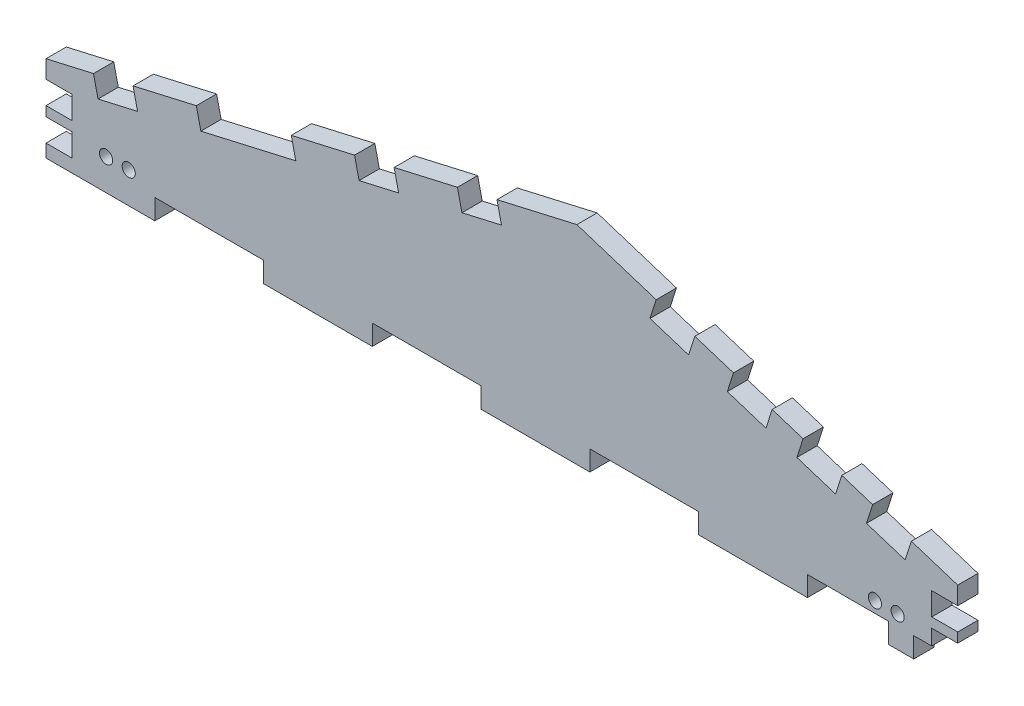
SolidWorks part; units mm, degrees
material "Maple"
ref_plane "Front Plane" through (0, 0, 0) normal (0, 0, 1) x (1, 0, 0)
ref_plane "Top Plane" through (0, 0, 0) normal (0, 1, 0) x (1, 0, 0)
ref_plane "Right Plane" through (0, 0, 0) normal (1, 0, 0) x (0, 0, -1)
sketch "Sketch2" plane through (0, 0, 0) normal (0, 0, 1) x (1, 0, 0)
  line L0 (11.7348, -6.731) -> (11.7348, 25.781)
  line L1 (-71.3232, -6.731) -> (71.3232, -6.731)
  line L2 (-71.3232, -6.731) -> (-71.3232, 6.731)
  line L3 (-71.3232, 6.731) -> (71.3232, 6.731)
  line L4 (71.3232, -6.731) -> (71.3232, 6.731)
  line L5 (-71.3232, -6.731) -> (71.3232, 6.731) construction
  line L6 (-71.3232, 6.731) -> (71.3232, -6.731) construction
  line L7 (-71.3232, 6.731) -> (11.7348, 25.781)
  line L8 (11.7348, 25.781) -> (71.3232, 6.731)
  line L9 (-71.3232, 6.731) -> (11.7348, 25.781)
  line L10 (71.3232, 6.731) -> (-71.3232, 6.731)
  line L11 (11.7348, 25.781) -> (71.3232, 6.731)
  line L12 (0, -17.8816) -> (0, 17.8816) construction
  line L13 (-71.3232, -4.699) -> (-67.2592, -4.699)
  line L14 (-71.3232, -4.699) -> (-71.3232, -1.143)
  line L15 (-71.3232, -1.143) -> (-67.2592, -1.143)
  line L16 (-67.2592, -4.699) -> (-67.2592, -1.143)
  line L17 (-71.3232, 0.381) -> (-67.2592, 0.381)
  line L18 (-71.3232, 0.381) -> (-71.3232, 3.937)
  line L19 (-71.3232, 3.937) -> (-67.2592, 3.937)
  line L20 (-67.2592, 0.381) -> (-67.2592, 3.937)
  line L22 (71.3232, 4.5729) -> (71.3232, 1.5826)
  line L29 (71.3232, -1.143) -> (67.2592, -1.143)
  line L30 (67.2592, -4.699) -> (67.2592, -1.143)
  line L31 (71.3232, -4.699) -> (67.2592, -4.699)
  line L32 (71.3232, -4.699) -> (71.3232, -1.143)
  line L33 (71.3232, 3.937) -> (67.2592, 3.937)
  line L34 (67.2592, 0.381) -> (67.2592, 3.937)
  line L35 (71.3232, 0.381) -> (67.2592, 0.381)
  line L36 (71.3232, 0.381) -> (71.3232, 3.937)
  point P0 (0, 0)
  dimension "D1" = 142.6464
  dimension "D2" = 13.462
  dimension "D3" = 32.512
  dimension "D4" = 83.058
  dimension "D5" = 4.064
  dimension "D6" = 4.064
  dimension "D7" = 3.556
  dimension "D8" = 3.556
  dimension "D9" = 1.524
  dimension "D10" = 2.032
extrude "Boss-Extrude1" add sketch "Sketch2" along normal blind 3.175 contours L7 L3 L0 | L8 L0 L3 | L4 L35 L34 L33 L22 L3 L0 L1 L31 L30 L29 | L20 L17 L2 L15 L16 L13 L1 L0 L3 L19
sketch "Sketch4" plane through (0, 0, 3.175) normal (0, 0, 1) x (1, 0, 0)
  line L0 (-71.3232, -6.731) -> (71.3232, -6.731) construction
  line L1 (-54.3052, -6.731) -> (-37.2872, -6.731)
  line L2 (-54.3052, -6.731) -> (-54.3052, -3.556)
  line L3 (-54.3052, -3.556) -> (-37.2872, -3.556)
  line L4 (-37.2872, -6.731) -> (-37.2872, -3.556)
  line L6 (-20.2692, -6.731) -> (-3.2512, -6.731)
  line L7 (-20.2692, -6.731) -> (-20.2692, -3.556)
  line L8 (-20.2692, -3.556) -> (-3.2512, -3.556)
  line L9 (-3.2512, -6.731) -> (-3.2512, -3.556)
  line L10 (13.7668, -6.731) -> (30.7848, -6.731)
  line L11 (13.7668, -6.731) -> (13.7668, -3.5869)
  line L12 (13.7668, -3.5869) -> (30.7848, -3.5869)
  line L13 (30.7848, -6.731) -> (30.7848, -3.5869)
  line L18 (-71.3232, -6.731) -> (-71.3232, -4.699) construction
  line L20 (73.2028, -6.731) -> (77.1398, -6.731)
  line L21 (73.2028, -6.731) -> (73.2028, -3.556)
  line L22 (73.2028, -3.556) -> (77.1398, -3.556)
  line L23 (77.1398, -6.731) -> (77.1398, -3.556)
  line L24 (47.8028, -6.731) -> (60.5028, -6.731)
  line L25 (47.8028, -6.731) -> (47.8028, -3.5869)
  line L26 (47.8028, -3.5869) -> (60.5028, -3.5869)
  line L27 (60.5028, -6.731) -> (60.5028, -3.5869)
  dimension "D1" = 17.018
  dimension "D2" = 17.018
  dimension "D3" = 17.018
  dimension "D4" = 17.018
  dimension "D5" = 17.018
  dimension "D6" = 17.018
  dimension "D7" = 3.175
  dimension "D8" = 3.175
  dimension "D9" = 3.937
  dimension "D10" = 3.175
  dimension "D11" = 12.7
  dimension "D12" = 12.7
  dimension "D13" = 17.018
extrude "Cut-Extrude1" cut sketch "Sketch4" against normal blind 3.175
sketch "Sketch5" plane through (0, 0, 3.175) normal (0, 0, 1) x (1, 0, 0)
  line L0 (60.5028, -6.731) -> (71.3232, -6.731) construction
  line L1 (64.4398, -6.731) -> (71.9567, -6.731)
  line L2 (64.4398, -6.731) -> (64.4398, -3.556)
  line L3 (64.4398, -3.556) -> (71.9567, -3.556)
  line L4 (71.9567, -6.731) -> (71.9567, -3.556)
  line L5 (60.5028, -6.731) -> (60.5028, -3.5869) construction
  dimension "D1" = 3.937
  dimension "D2" = 3.175
extrude "Cut-Extrude2" cut sketch "Sketch5" against normal blind 3.175
sketch "Sketch6" plane through (0, 0, 3.175) normal (0, 0, 1) x (1, 0, 0)
  line L1 (-71.3232, 3.937) -> (-71.3232, 6.731) construction
  line L2 (-71.3232, -6.731) -> (-54.3052, -6.731) construction
  line L3 (0, -1.7463) -> (0, 1.7463) construction
  circle A0 centre (-61.9252, -1.8542) radius 1.0287
  circle A1 centre (-58.3786, -1.8542) radius 1.0287
  circle A2 centre (61.9252, -1.8542) radius 1.0287
  circle A3 centre (58.3786, -1.8542) radius 1.0287
  dimension "D1" = 2.0574
  dimension "D3" = 4.8768
  dimension "D4" = 2.0574
  dimension "D2" = 9.398
extrude "Cut-Extrude3" cut sketch "Sketch6" against normal blind 3.175
sketch "Sketch7" plane through (0, 0, 3.175) normal (0, 0, 1) x (1, 0, 0)
  line L0 (-63.896, 8.4345) -> (-57.7068, 9.854)
  line L1 (-63.896, 8.4345) -> (-63.1863, 5.3398)
  line L2 (-57.7068, 9.854) -> (-56.997, 6.7594)
  line L3 (-63.1863, 5.3398) -> (-56.997, 6.7594)
  line L4 (-71.3232, 6.731) -> (11.7348, 25.781) construction
  line L5 (-47.8039, 12.1253) -> (-32.9496, 15.5323)
  line L6 (-47.8039, 12.1253) -> (-47.0941, 9.0307)
  line L7 (-32.9496, 15.5323) -> (-32.2398, 12.4376)
  line L8 (-47.0941, 9.0307) -> (-32.2398, 12.4376)
  line L9 (-23.0467, 17.8036) -> (-16.8574, 19.2232)
  line L10 (-23.0467, 17.8036) -> (-22.3369, 14.7089)
  line L11 (-16.8574, 19.2232) -> (-16.1476, 16.1285)
  line L12 (-22.3369, 14.7089) -> (-16.1476, 16.1285)
  line L13 (-6.9546, 21.4945) -> (-0.7653, 22.914)
  line L14 (-6.9546, 21.4945) -> (-6.2448, 18.3998)
  line L15 (-0.7653, 22.914) -> (-0.0555, 19.8194)
  line L16 (-6.2448, 18.3998) -> (-0.0555, 19.8194)
  line L17 (24.1454, 21.8134) -> (30.1939, 19.8798)
  line L18 (24.1454, 21.8134) -> (23.1786, 18.7892)
  line L19 (30.1939, 19.8798) -> (29.227, 16.8555)
  line L20 (23.1786, 18.7892) -> (29.227, 16.8555)
  line L21 (11.7348, 25.781) -> (71.3232, 6.731) construction
  line L22 (36.2423, 17.9461) -> (42.2907, 16.0125)
  line L23 (36.2423, 17.9461) -> (35.2755, 14.9219)
  line L24 (42.2907, 16.0125) -> (41.3239, 12.9883)
  line L25 (35.2755, 14.9219) -> (41.3239, 12.9883)
  line L26 (47.1295, 14.4656) -> (53.1779, 12.5319)
  line L27 (47.1295, 14.4656) -> (46.1627, 11.4414)
  line L28 (53.1779, 12.5319) -> (52.2111, 9.5077)
  line L29 (46.1627, 11.4414) -> (52.2111, 9.5077)
  line L30 (58.0166, 10.985) -> (64.0651, 9.0514)
  line L31 (58.0166, 10.985) -> (57.0498, 7.9608)
  line L32 (64.0651, 9.0514) -> (63.0983, 6.0272)
  line L33 (57.0498, 7.9608) -> (63.0983, 6.0272)
  dimension "D1" = 3.175
  dimension "D2" = 3.175
  dimension "D3" = 3.175
  dimension "D4" = 3.175
  dimension "D5" = 3.175
  dimension "D6" = 3.175
  dimension "D7" = 3.175
  dimension "D8" = 3.175
  dimension "D9" = 7.62
  dimension "D10" = 6.35
  dimension "D11" = 5.08
  dimension "D12" = 6.35
  dimension "D13" = 5.08
  dimension "D14" = 6.35
  dimension "D15" = 6.35
  dimension "D16" = 6.35
  dimension "D17" = 7.62
  dimension "D18" = 6.35
  dimension "D19" = 10.16
  dimension "D20" = 10.16
  dimension "D21" = 10.16
  dimension "D22" = 6.35
  dimension "D23" = 6.35
  dimension "D24" = 15.24
extrude "Cut-Extrude4" cut sketch "Sketch7" against normal blind 4.064
